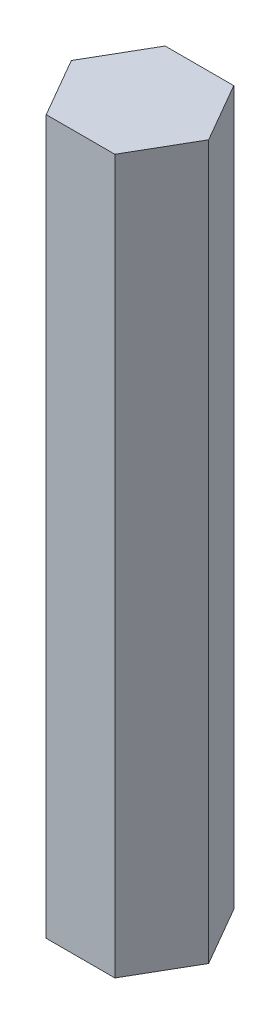
SolidWorks part; units mm, degrees
material "1060 Alloy"
ref_plane "Front Plane" through (0, 0, 0) normal (0, 0, 1) x (1, 0, 0)
ref_plane "Top Plane" through (0, 0, 0) normal (0, 1, 0) x (1, 0, 0)
ref_plane "Right Plane" through (0, 0, 0) normal (1, 0, 0) x (0, 0, -1)
sketch "Sketch1" plane through (0, 0, 0) normal (0, 1, 0) x (1, 0, 0)
  line L1 (7.3323, 0) -> (3.6662, 6.35)
  line L2 (3.6662, 6.35) -> (-3.6662, 6.35)
  line L3 (-3.6662, 6.35) -> (-7.3323, 0)
  line L4 (-7.3323, 0) -> (-3.6662, -6.35)
  line L5 (-3.6662, -6.35) -> (3.6662, -6.35)
  line L6 (3.6662, -6.35) -> (7.3323, 0)
  circle A0 centre (0, 0) radius 6.35 construction
  dimension "D1" = 12.7
extrude "Boss-Extrude1" add sketch "Sketch1" along normal blind 76.2
other "PropertyManager"
